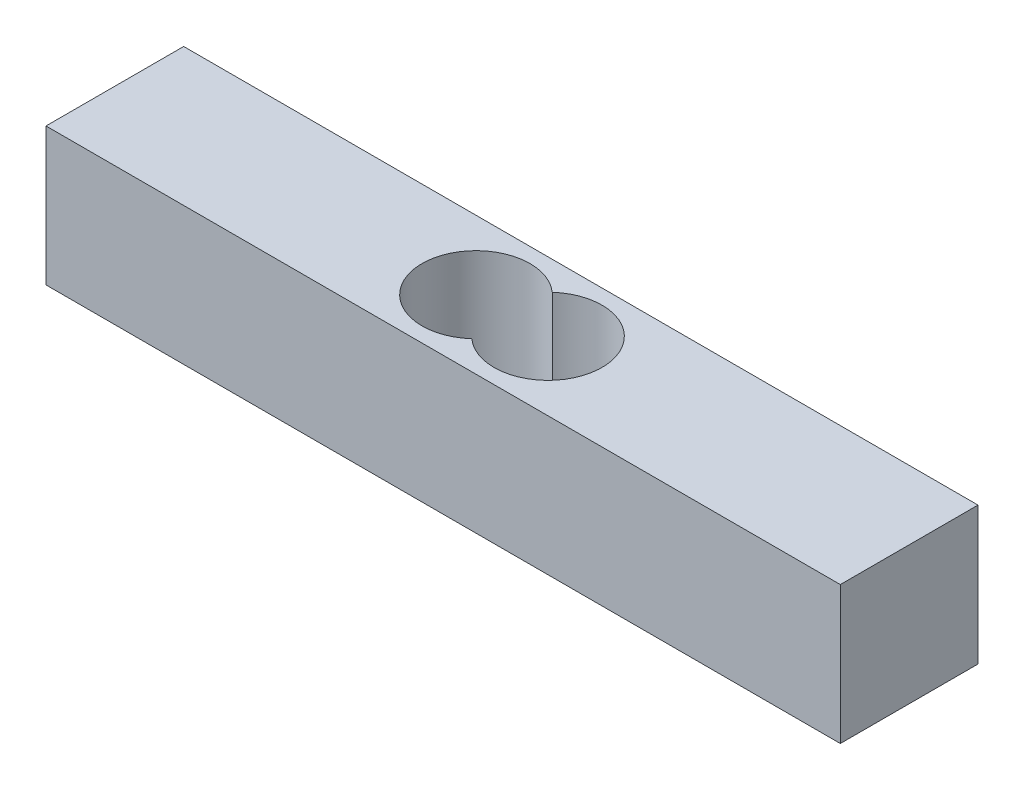
SolidWorks part; units mm, degrees
ref_plane "Front Plane" through (0, 0, 0) normal (0, 0, 1) x (1, 0, 0)
ref_plane "Top Plane" through (0, 0, 0) normal (0, 1, 0) x (1, 0, 0)
ref_plane "Right Plane" through (0, 0, 0) normal (1, 0, 0) x (0, 0, -1)
sketch "Sketch1" plane through (0, 0, 0) normal (0, 1, 0) x (1, 0, 0)
  line L0 (-37.5, 0) -> (-8.5, 0) construction
  line L1 (-37.5, 6.5) -> (37.5, 6.5)
  line L2 (-37.5, 6.5) -> (-37.5, -6.5)
  line L3 (-37.5, -6.5) -> (37.5, -6.5)
  line L4 (37.5, 6.5) -> (37.5, -6.5)
  line L6 (0, 3.8013) -> (0, 9.0048) construction
  line L7 (37.5, 0) -> (8.5, 0) construction
  arc A0 (0, 3.8013) -> (0, -3.8013) centre (-3.4, 0) ccw
  arc A1 (0, 3.8013) -> (0, -3.8013) centre (3.4, 0) cw
  dimension "D1" = 75
  dimension "D2" = 13
  dimension "D4" = 29
extrude "Boss-Extrude1" add sketch "Sketch1" along normal blind 13
